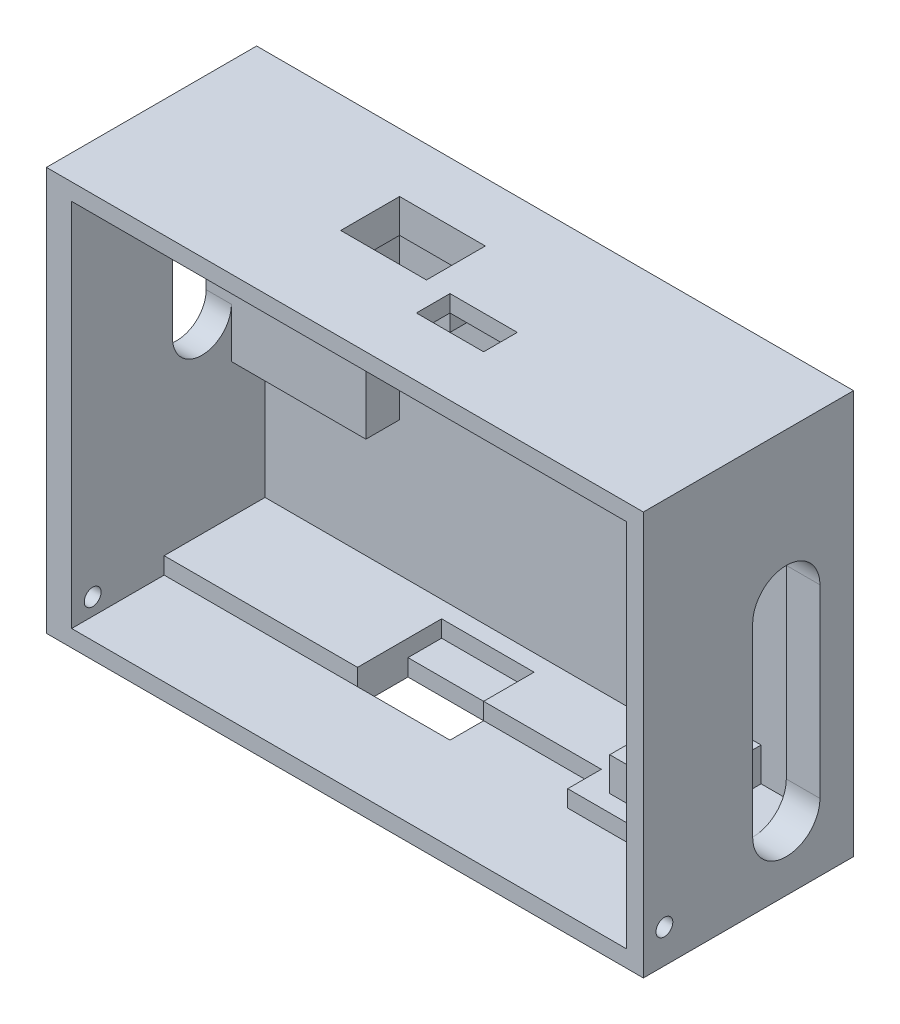
SolidWorks part; units mm, degrees
ref_plane "前视基准面" through (0, 0, 0) normal (0, 0, 1) x (1, 0, 0)
ref_plane "上视基准面" through (0, 0, 0) normal (0, 1, 0) x (1, 0, 0)
ref_plane "右视基准面" through (0, 0, 0) normal (1, 0, 0) x (0, 0, -1)
sketch "草图1" plane through (0, 0, 0) normal (0, 0, 1) x (1, 0, 0)
  line L5 (-17.75, 12) -> (17.75, 12)
  line L6 (-17.75, 12) -> (-17.75, -12)
  line L7 (-17.75, -12) -> (17.75, -12)
  line L8 (17.75, 12) -> (17.75, -12)
  line L9 (-17.75, 12) -> (17.75, -12) construction
  line L10 (-17.75, -12) -> (17.75, 12) construction
  point P0 (0, 0)
  dimension "D1" = 35.5
  dimension "D2" = 24
extrude "凸台-拉伸1" add sketch "草图1" along normal blind 12.5
sketch "草图2" plane through (0, 0, 12.5) normal (0, 0, 1) x (1, 0, 0)
  line L5 (-16.25, 11) -> (16.75, -11) construction
  line L6 (-16.25, -11) -> (16.75, 11) construction
  line L9 (-17.75, 12) -> (-17.75, -12) construction
  line L10 (-16.25, 11) -> (16.75, 11)
  line L11 (-16.25, 11) -> (-16.25, -11)
  line L12 (-16.25, -11) -> (16.75, -11)
  line L13 (16.75, 11) -> (16.75, -11)
  line L15 (17.75, 12) -> (-17.75, 12) construction
  line L16 (17.75, -12) -> (17.75, 12) construction
  point P0 (0, 0)
  dimension "D1" = 1.5
  dimension "D2" = 1
  dimension "D3" = 1
  dimension "D4" = 22
extrude "切除-拉伸1" cut sketch "草图2" against normal blind 11.5
sketch "草图3" plane through (-17.75, 0, 0) normal (-1, 0, 0) x (0, 0, 1)
  line L0 (4.75, 7.45) -> (4.75, 0.95) construction
  line L1 (6.5, 7.45) -> (6.5, 0.95)
  line L2 (3, 7.45) -> (3, 0.95)
  line L3 (0, 12) -> (0, -12) construction
  line L4 (12.5, 12) -> (0, 12) construction
  arc A0 (6.5, 7.45) -> (3, 7.45) centre (4.75, 7.45) ccw
  arc A1 (3, 0.95) -> (6.5, 0.95) centre (4.75, 0.95) ccw
  point P2 (4.75, 4.2)
  dimension "D3" = 6.5
  dimension "D4" = 4.55
  dimension "D1" = 3
  dimension "D2" = 3.5
extrude "切除-拉伸2" cut sketch "草图3" against normal blind 2
sketch "草图6" plane through (0, 0, 1) normal (0, 0, 1) x (1, 0, 0)
  line L14 (-16.25, 10) -> (15.75, 10)
  line L15 (-16.25, 11) -> (-16.25, -11) construction
  line L16 (15.75, 10) -> (15.75, -10)
  line L17 (15.75, -10) -> (-16.25, -10)
  line L18 (-16.25, -10) -> (-16.25, -11)
  line L19 (-16.25, -11) -> (16.75, -11)
  line L20 (16.75, -11) -> (16.75, 11)
  line L21 (16.75, 11) -> (-16.25, 11)
  line L22 (-16.25, 11) -> (-16.25, 10)
  dimension "D1" = 1
  dimension "D2" = 1
  dimension "D3" = 1
extrude "凸台-拉伸2" add sketch "草图6" along normal blind 6
sketch "草图7" plane through (0, 0, 1) normal (0, 0, 1) x (1, 0, 0)
  line L5 (9.25, -10) -> (13.25, -10)
  line L6 (9.25, -10) -> (9.25, -8)
  line L7 (9.25, -8) -> (13.25, -8)
  line L8 (13.25, -10) -> (13.25, -8)
  line L16 (15.75, 10) -> (15.75, -10) construction
  line L23 (15.75, 10) -> (10.75, 10)
  line L24 (15.75, 10) -> (15.75, 8)
  line L25 (15.75, 8) -> (10.75, 8)
  line L26 (10.75, 10) -> (10.75, 8)
  dimension "D1" = 2.5
  dimension "D3" = 5
  dimension "D4" = 2
  dimension "D5" = 4
  dimension "D8" = 2
extrude "凸台-拉伸3" add sketch "草图7" along normal blind 5
sketch "草图10" plane through (15.75, 0, 0) normal (-1, 0, 0) x (0, 0, 1)
  line L0 (4, -8) -> (4, 3) construction
  line L1 (2, -8) -> (2, 3)
  line L2 (6, -8) -> (6, 3)
  line L3 (7, -11) -> (7, 11) construction
  line L4 (12.5, -12) -> (0, -12) construction
  arc A0 (2, -8) -> (6, -8) centre (4, -8) ccw
  arc A1 (6, 3) -> (2, 3) centre (4, 3) ccw
  point P2 (4, -2.5)
  point P7 (4, 5)
  point P8 (4, -10)
  dimension "D2" = 15
  dimension "D1" = 11
  dimension "D3" = 1
  dimension "D4" = 2
extrude "切除-拉伸4" cut sketch "草图10" against normal blind 2
sketch "草图11" plane through (17.75, 0, 0) normal (1, 0, 0) x (0, 0, -1)
  line L0 (-12.5, -12) -> (0, -12) construction
  line L1 (-12.5, -12) -> (-12.5, 12) construction
  circle A0 centre (-11.25, -10) radius 0.5
  dimension "D1" = 1
  dimension "D3" = 1.25
  dimension "D2" = 2
extrude "切除-拉伸5" cut sketch "草图11" against normal blind 35
sketch "草图12" plane through (0, 0, 7) normal (0, 0, 1) x (1, 0, 0)
  line L8 (15.75, -10) -> (-16.25, -10) construction
  line L9 (-4.75, -10) -> (0.75, -10)
  line L10 (-4.75, -10) -> (-4.75, -11)
  line L11 (-4.75, -11) -> (0.75, -11)
  line L12 (0.75, -10) -> (0.75, -11)
  line L13 (-16.25, -11) -> (16.75, -11) construction
  line L14 (-16.25, -10) -> (-16.25, -11) construction
  line L15 (-16.25, 11) -> (-16.25, -11) construction
  dimension "D1" = 11.5
  dimension "D2" = 17
extrude "切除-拉伸6" cut sketch "草图12" against normal blind 5
sketch "草图15" plane through (0, -11, 0) normal (0, 1, 0) x (1, 0, 0)
  line L0 (0.75, -2) -> (0.75, -7) construction
  line L1 (-4.75, -7) -> (0.75, -7)
  line L2 (-4.75, -7) -> (-4.75, -4)
  line L3 (-4.75, -4) -> (0.75, -4)
  line L4 (0.75, -7) -> (0.75, -4)
  dimension "D1" = 3
extrude "切除-拉伸7" cut sketch "草图15" against normal blind 5
sketch "草图16" plane through (0, 10, 0) normal (0, -1, 0) x (1, 0, 0)
  line L0 (-16.25, 7) -> (15.75, 7) construction
  line L1 (-5.75, 7) -> (-0.65, 7)
  line L2 (-5.75, 7) -> (-5.75, 3.5)
  line L3 (-5.75, 3.5) -> (-0.65, 3.5)
  line L4 (-0.65, 7) -> (-0.65, 3.5)
  line L5 (-17.75, 12.5) -> (-17.75, 0) construction
  dimension "D1" = 12
  dimension "D2" = 17.1
  dimension "D3" = 3.5
extrude "切除-拉伸8" cut sketch "草图16" against normal blind 5
sketch "草图18" plane through (0, 0, 7) normal (0, 0, 1) x (1, 0, 0)
  line L0 (15.75, -10) -> (0.75, -10) construction
  line L1 (0.75, -11) -> (7.75, -11)
  line L2 (0.75, -11) -> (0.75, -10)
  line L3 (0.75, -10) -> (7.75, -10)
  line L4 (7.75, -11) -> (7.75, -10)
  dimension "D1" = 7
extrude "FPC排线间隙" cut sketch "草图18" against normal blind 2
sketch "草图19" plane through (0, 0, 1) normal (0, 0, 1) x (1, 0, 0)
  line L1 (-16.25, 10) -> (-8.25, 10)
  line L2 (-16.25, 10) -> (-16.25, -2)
  line L3 (-16.25, -2) -> (-8.25, -2)
  line L4 (-8.25, 10) -> (-8.25, -2)
  dimension "D1" = 8
  dimension "D2" = 12
extrude "USB支撑" add sketch "草图19" along normal blind 2
sketch "草图20" plane through (0, 12, 0) normal (0, 1, 0) x (1, 0, 0)
  line L0 (17.75, -12.5) -> (-17.75, -12.5) construction
  line L1 (0.75, -7) -> (4.75, -7)
  line L2 (0.75, -7) -> (0.75, -9)
  line L3 (0.75, -9) -> (4.75, -9)
  line L4 (4.75, -7) -> (4.75, -9)
  line L5 (17.75, -12.5) -> (17.75, 0) construction
  dimension "D1" = 4
  dimension "D2" = 2
  dimension "D3" = 3.5
  dimension "D4" = 13
extrude "切除-拉伸10" cut sketch "草图20" against normal blind 2
sketch "草图21" plane through (0, 0, 7) normal (0, 0, 1) x (1, 0, 0)
  line L0 (-8.25, 10) -> (10.75, 10) construction
  line L1 (0.75, 11) -> (4.75, 11)
  line L2 (0.75, 11) -> (0.75, 10)
  line L3 (0.75, 10) -> (4.75, 10)
  line L4 (4.75, 11) -> (4.75, 10)
  dimension "D1" = 4
extrude "切除-拉伸11" cut sketch "草图21" against normal blind 2
